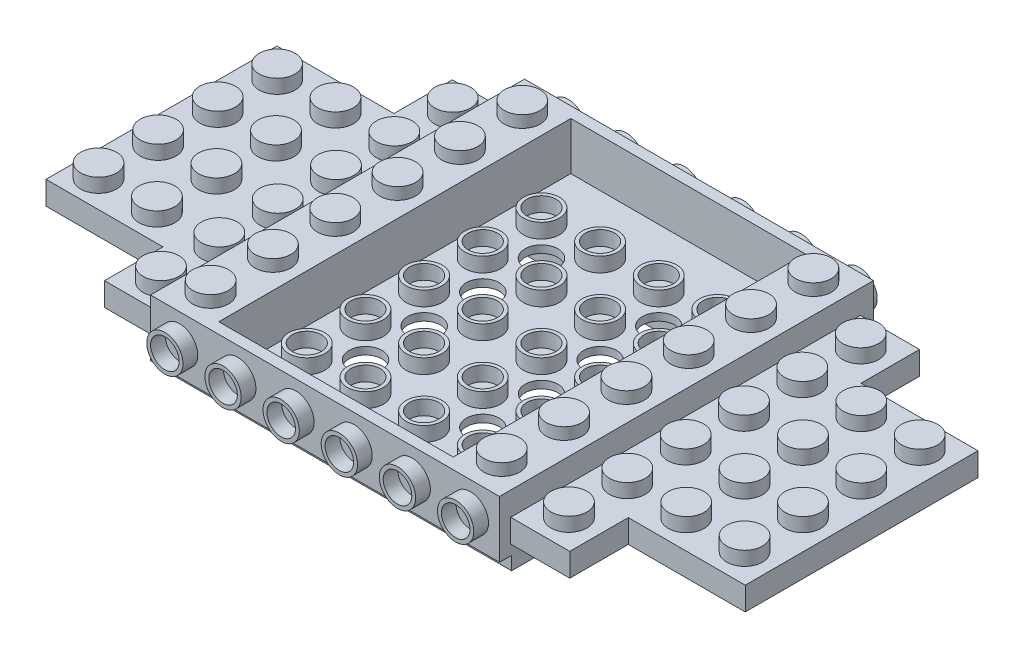
SolidWorks part; units mm, degrees
ref_plane "Front Plane" through (0, 0, 0) normal (0, 0, 1) x (1, 0, 0)
ref_plane "Top Plane" through (0, 0, 0) normal (0, 1, 0) x (1, 0, 0)
ref_plane "Right Plane" through (0, 0, 0) normal (1, 0, 0) x (0, 0, -1)
sketch "Sketch2" plane through (0, 0, 0) normal (0, 1, 0) x (1, 0, 0)
  line L1 (-23.86, 25.57) -> (23.86, 25.57)
  line L2 (-23.86, 25.57) -> (-23.86, -25.57)
  line L3 (-23.86, -25.57) -> (23.86, -25.57)
  line L4 (23.86, 25.57) -> (23.86, -25.57)
  line L5 (-23.86, 25.57) -> (23.86, -25.57) construction
  line L6 (-23.86, -25.57) -> (23.86, 25.57) construction
  point P0 (0, 0)
  dimension "D1" = 51.14
  dimension "D2" = 47.72
extrude "Boss-Extrude1" add sketch "Sketch2" against normal blind 9.64
sketch "Sketch3" plane through (0, 0, 0) normal (0, 1, 0) x (1, 0, 0)
  line L0 (-23.86, 25.57) -> (-23.86, -25.57) construction
  line L1 (-16.03, 24.07) -> (16.03, 24.07)
  line L2 (-16.03, 24.07) -> (-16.03, -24.07)
  line L3 (-16.03, -24.07) -> (16.03, -24.07)
  line L4 (16.03, 24.07) -> (16.03, -24.07)
  line L5 (-16.03, 24.07) -> (16.03, -24.07) construction
  line L6 (-16.03, -24.07) -> (16.03, 24.07) construction
  line L7 (23.86, 25.57) -> (-23.86, 25.57) construction
  point P0 (0, 0)
  dimension "D1" = 7.83
  dimension "D2" = 1.5
extrude "Cut-Extrude1" cut sketch "Sketch3" against normal blind 6.53
sketch "Sketch4" plane through (23.86, 0, 0) normal (1, 0, 0) x (0, 0, -1)
  line L0 (-32.1055, -4.82) -> (30.0315, -4.82) construction
  line L2 (-25.57, 0) -> (25.57, 0) construction
  line L3 (-24.04, -3.23) -> (-24.04, -6.41)
  line L4 (23.79, -3.23) -> (23.79, -6.41)
  line L5 (25.57, -9.64) -> (25.57, 0) construction
  line L6 (-24.04, -6.41) -> (23.79, -6.41)
  line L7 (-24.04, -3.23) -> (23.79, -3.23)
  point P6 (-24.04, -4.82)
  point P9 (23.79, -4.82)
  dimension "D1" = 4.82
  dimension "D2" = 3.18
  dimension "D3" = 3.18
  dimension "D4" = 47.83
  dimension "D5" = 1.78
extrude "Boss-Extrude2" add sketch "Sketch4" along normal blind 8.08
sketch "Sketch5" plane through (23.86, 0, 0) normal (1, 0, 0) x (0, 0, -1)
  line L0 (-25.57, -7.8) -> (-23.91, -7.8)
  line L1 (-25.57, -9.64) -> (-25.57, 0) construction
  line L2 (-23.91, -7.8) -> (-23.91, -9.64)
  line L3 (-25.57, -9.64) -> (25.57, -9.64) construction
  line L4 (0, 5.3017) -> (0, -15.0404) construction
  line L5 (23.91, -7.8) -> (23.91, -9.64)
  line L6 (25.57, -7.8) -> (23.91, -7.8)
  line L7 (-25.57, -7.8) -> (-25.57, -9.64)
  line L8 (-25.57, -9.64) -> (-23.91, -9.64)
  line L9 (23.91, -9.64) -> (25.57, -9.64)
  line L10 (25.57, -9.64) -> (25.57, -7.8)
  dimension "D1" = 1.66
  dimension "D2" = 1.84
extrude "Cut-Extrude2" cut sketch "Sketch5" against normal through all
sketch "Sketch6" plane through (31.94, 0, 0) normal (1, 0, 0) x (0, 0, -1)
  line L0 (-16.04, -3.23) -> (-16.04, -6.41)
  line L1 (23.79, -3.23) -> (-24.04, -3.23) construction
  line L2 (-24.04, -6.41) -> (23.79, -6.41) construction
  line L3 (-16.04, -6.41) -> (15.79, -6.41)
  line L4 (-24.04, -6.41) -> (23.79, -6.41) construction
  line L5 (15.79, -6.41) -> (15.79, -3.23)
  line L6 (23.79, -3.23) -> (-24.04, -3.23) construction
  line L7 (15.79, -3.23) -> (-16.04, -3.23)
  line L8 (23.79, -6.41) -> (23.79, -3.23) construction
  line L9 (-24.04, -3.23) -> (-24.04, -6.41) construction
  point P14 (23.79, -4.82)
  dimension "D1" = 8
  dimension "D2" = 8
extrude "Boss-Extrude3" add sketch "Sketch6" along normal blind 16
sketch "Sketch8" plane through (-23.86, 0, 0) normal (-1, 0, 0) x (0, 0, 1)
  line L0 (-23.79, -4.82) -> (23.79, -4.82) construction
  line L1 (-25.57, 0) -> (25.57, 0) construction
  line L2 (-25.57, -7.8) -> (-25.57, 0) construction
  line L4 (-23.79, -3.23) -> (-23.79, -6.41)
  line L5 (-23.79, -6.41) -> (23.79, -6.41)
  line L6 (23.79, -6.41) -> (23.79, -3.23)
  line L7 (23.79, -3.23) -> (-23.79, -3.23)
  point P6 (0, -4.82)
  point P13 (-23.79, -4.82)
  dimension "D1" = 4.82
  dimension "D2" = 1.78
  dimension "D3" = 3.18
extrude "Boss-Extrude4" add sketch "Sketch8" along normal blind 8.08
sketch "Sketch9" plane through (-31.94, 0, 0) normal (-1, 0, 0) x (0, 0, 1)
  line L0 (-15.79, -3.23) -> (-15.79, -6.41)
  line L1 (23.79, -3.23) -> (-23.79, -3.23) construction
  line L2 (-23.79, -6.41) -> (23.79, -6.41) construction
  line L3 (-15.79, -6.41) -> (15.79, -6.41)
  line L4 (15.79, -6.41) -> (15.79, -3.23)
  line L5 (23.79, -3.23) -> (-23.79, -3.23) construction
  line L6 (15.79, -3.23) -> (-15.79, -3.23)
  line L7 (-23.79, -3.23) -> (-23.79, -6.41) construction
  line L8 (23.79, -6.41) -> (23.79, -3.23) construction
  dimension "D1" = 8
  dimension "D2" = 8
extrude "Boss-Extrude5" add sketch "Sketch9" along normal blind 16
sketch "Sketch12" plane through (0, -3.23, 0) normal (0, 1, 0) x (1, 0, 0)
  line L1 (-31.94, 15.79) -> (-31.94, 23.79) construction
  line L2 (-31.94, 23.79) -> (-23.86, 23.79) construction
  line L4 (-47.94, -15.79) -> (-47.94, 15.79) construction
  circle A0 centre (-27.9, 19.79) radius 2.455
  circle A1 centre (-27.9, 11.8117) radius 2.455
  circle A2 centre (-27.9, 3.8333) radius 2.455
  circle A3 centre (-27.9, -4.145) radius 2.455
  circle A4 centre (-27.9, -12.1233) radius 2.455
  circle A5 centre (-27.9, -20.1017) radius 2.455
  circle A6 centre (-43.9275, 11.8117) radius 2.455
  circle A7 centre (-35.9475, 11.8117) radius 2.455
  circle A8 centre (-36.1106, 3.8333) radius 2.455
  circle A9 centre (-36.2737, -4.145) radius 2.455
  circle A10 centre (-36.4368, -12.1233) radius 2.455
  circle A11 centre (-44.0906, 3.8333) radius 2.455
  circle A12 centre (-44.2537, -4.145) radius 2.455
  circle A13 centre (-44.4168, -12.1233) radius 2.455
  dimension "D3" = 4.91
  dimension "D5" = 7.9783
  dimension "D6" = 4.91
  dimension "D7" = 4.0125
  dimension "D10" = 7.98
  dimension "D11" = 7.98
  dimension "D1" = 4.04
  dimension "D2" = 4
  dimension "D4" = 6
  dimension "D8" = 2
  dimension "D9" = 4
extrude "Boss-Extrude6" add sketch "Sketch12" along normal blind 1.91
sketch "Sketch13" plane through (0, -3.23, 0) normal (0, 1, 0) x (1, 0, 0)
  line L1 (31.94, 23.79) -> (31.94, 15.79) construction
  line L2 (31.94, 23.79) -> (23.86, 23.79) construction
  line L5 (47.94, 15.79) -> (47.94, -16.04) construction
  line L6 (47.94, -16.04) -> (31.94, -16.04) construction
  circle A0 centre (27.9, 19.79) radius 2.455
  circle A2 centre (27.9, 11.81) radius 2.455
  circle A3 centre (27.9, 3.83) radius 2.455
  circle A4 centre (27.9, -4.15) radius 2.455
  circle A5 centre (27.9, -12.13) radius 2.455
  circle A6 centre (27.9, -20.11) radius 2.455
  circle A7 centre (43.94, 11.81) radius 2.455
  circle A8 centre (35.96, 11.81) radius 2.455
  circle A9 centre (35.96, 3.83) radius 2.455
  circle A10 centre (35.96, -4.15) radius 2.455
  circle A11 centre (35.96, -12.13) radius 2.455
  circle A12 centre (43.94, 3.83) radius 2.455
  circle A13 centre (43.94, -4.15) radius 2.455
  circle A14 centre (43.94, -12.13) radius 2.455
  dimension "D1" = 4.04
  dimension "D2" = 4.91
  dimension "D6" = 4.91
  dimension "D7" = 4
  dimension "D11" = 7.98
  dimension "D12" = 7.98
  dimension "D8" = 3.91
  dimension "D3" = 4
  dimension "D4" = 6
  dimension "D9" = 2
  dimension "D10" = 4
extrude "Boss-Extrude7" add sketch "Sketch13" along normal blind 1.91
sketch "Sketch14" plane through (0, -6.41, 0) normal (0, -1, 0) x (1, 0, 0)
  line L0 (-46.34, 14.19) -> (-23.86, 14.19)
  line L1 (-23.86, -23.79) -> (-23.86, 23.79) construction
  line L2 (-46.34, 14.19) -> (-46.34, -14.19)
  line L3 (-46.34, -14.19) -> (-23.86, -14.19)
  line L4 (-23.86, -14.19) -> (-23.86, 14.19)
  line L5 (-47.94, 15.79) -> (-31.94, 15.79) construction
  line L6 (-47.94, -15.79) -> (-31.94, -15.79) construction
  line L7 (-47.94, -15.79) -> (-47.94, 15.79) construction
  dimension "D1" = 1.6
  dimension "D2" = 1.6
  dimension "D3" = 1.6
extrude "Cut-Extrude3" cut sketch "Sketch14" against normal blind 2.25
sketch "Sketch17" plane through (0, -6.41, 0) normal (0, -1, 0) x (1, 0, 0)
  line L0 (-23.86, 15.79) -> (-30.34, 15.79)
  line L1 (-23.86, 14.19) -> (-23.86, 23.79) construction
  line L2 (-30.34, 15.79) -> (-30.34, 22.19)
  line L3 (-30.34, 22.19) -> (-23.86, 22.19)
  line L5 (-31.94, 23.79) -> (-23.86, 23.79) construction
  line L6 (-31.94, 15.79) -> (-31.94, 23.79) construction
  line L7 (-23.86, 14.19) -> (-46.34, 14.19) construction
  line L8 (-23.86, 22.19) -> (-23.86, 15.79)
  line L9 (-59.2264, 0) -> (-14.3327, 0) construction
  line L10 (-23.86, -22.19) -> (-23.86, -15.79)
  line L11 (-23.86, -15.79) -> (-30.34, -15.79)
  line L12 (-30.34, -15.79) -> (-30.34, -22.19)
  line L13 (-30.34, -22.19) -> (-23.86, -22.19)
  dimension "D1" = 1.6
  dimension "D2" = 1.6
  dimension "D3" = 1.6
extrude "Cut-Extrude7" cut sketch "Sketch17" against normal blind 2.25
sketch "Sketch18" plane through (0, -6.41, 0) normal (0, -1, 0) x (1, 0, 0)
  line L0 (23.86, 14.44) -> (46.34, 14.44)
  line L1 (23.86, 24.04) -> (23.86, -23.79) construction
  line L2 (46.34, 14.44) -> (46.34, -14.19)
  line L3 (46.34, -14.19) -> (23.86, -14.19)
  line L4 (23.86, 23.91) -> (23.86, -23.91) construction
  line L5 (23.86, -14.19) -> (23.86, 14.44)
  line L6 (47.94, 16.04) -> (31.94, 16.04) construction
  line L7 (47.94, -15.79) -> (31.94, -15.79) construction
  line L8 (47.94, 16.04) -> (47.94, -15.79) construction
  line L9 (23.86, 22.44) -> (30.34, 22.44)
  line L10 (30.34, 22.44) -> (30.34, 16.04)
  line L11 (30.34, 16.04) -> (23.86, 16.04)
  line L12 (23.86, 16.04) -> (23.86, 22.44)
  line L13 (31.94, 24.04) -> (31.94, 16.04) construction
  line L14 (31.94, 24.04) -> (23.86, 24.04) construction
  line L15 (11.7115, 0) -> (59.8869, 0) construction
  line L16 (23.86, -16.04) -> (23.86, -22.44)
  line L17 (30.34, -16.04) -> (23.86, -16.04)
  line L18 (30.34, -22.44) -> (30.34, -16.04)
  line L19 (23.86, -22.44) -> (30.34, -22.44)
  point P16 (27.1, 16.04)
  point P19 (39.94, 16.04)
  dimension "D1" = 1.6
  dimension "D2" = 1.6
  dimension "D3" = 1.6
  dimension "D4" = 1.6
  dimension "D5" = 1.6
extrude "Cut-Extrude8" cut sketch "Sketch18" against normal blind 2.25
sketch "Sketch20" plane through (0, -4.16, 0) normal (0, -1, 0) x (1, 0, 0)
  line L0 (31.94, 24.04) -> (23.86, 24.04) construction
  line L1 (31.94, 24.04) -> (31.94, 16.04) construction
  circle A0 centre (27.9, 20.04) radius 0.855
  circle A1 centre (27.9, 12.06) radius 0.855
  circle A2 centre (27.9, 4.08) radius 0.855
  circle A3 centre (27.9, -3.9) radius 0.855
  circle A4 centre (27.9, -11.88) radius 0.855
  circle A5 centre (27.9, -19.86) radius 0.855
  circle A6 centre (35.88, -11.88) radius 0.855
  circle A7 centre (35.88, -3.9) radius 0.855
  circle A8 centre (43.86, -11.88) radius 0.855
  circle A9 centre (43.86, -3.9) radius 0.855
  circle A10 centre (35.88, 4.08) radius 0.855
  circle A11 centre (35.88, 12.06) radius 0.855
  circle A12 centre (43.86, 4.08) radius 0.855
  circle A13 centre (43.86, 12.06) radius 0.855
  dimension "D1" = 1.71
  dimension "D3" = 4.04
  dimension "D5" = 7.98
  dimension "D8" = 7.98
  dimension "D9" = 7.98
  dimension "D2" = 4
  dimension "D4" = 6
  dimension "D6" = 3
  dimension "D7" = 3
extrude "Cut-Extrude9" cut sketch "Sketch20" against normal blind 1.64
sketch "Sketch21" plane through (0, -4.16, 0) normal (0, -1, 0) x (1, 0, 0)
  circle A1 centre (-27.9, -19.79) radius 0.855
  circle A3 centre (-27.9, -11.81) radius 0.855
  circle A4 centre (-27.9, -3.83) radius 0.855
  circle A5 centre (-27.9, 4.15) radius 0.855
  circle A6 centre (-27.9, 12.13) radius 0.855
  circle A7 centre (-27.9, 20.11) radius 0.855
  circle A8 centre (-43.9275, -11.8117) radius 0.855
  circle A9 centre (-43.9275, -3.8317) radius 0.855
  circle A10 centre (-43.9275, 4.1483) radius 0.855
  circle A11 centre (-43.9275, 12.1283) radius 0.855
  circle A12 centre (-35.9475, -3.8317) radius 0.855
  circle A13 centre (-35.9475, 4.1483) radius 0.855
  circle A14 centre (-35.9475, 12.1283) radius 0.855
  circle A15 centre (-35.9475, -11.8117) radius 0.855
  dimension "D1" = 1.71
  dimension "D3" = 7.98
  dimension "D4" = 1.71
  dimension "D7" = 7.98
  dimension "D8" = 7.98
  dimension "D2" = 6
  dimension "D5" = 4
  dimension "D6" = 2
extrude "Cut-Extrude10" cut sketch "Sketch21" against normal blind 1.64
sketch "Sketch22" plane through (0, 0, -25.57) normal (0, 0, -1) x (-1, 0, 0)
  line L1 (-23.86, 0) -> (23.86, 0) construction
  line L2 (-23.86, -7.8) -> (-23.86, 0) construction
  circle A0 centre (-19.8833, -3.9) radius 2.48
  circle A1 centre (-19.8833, -3.9) radius 1.955
  circle A2 centre (-11.93, -3.9) radius 1.955
  circle A3 centre (-11.93, -3.9) radius 2.48
  circle A4 centre (-3.9767, -3.9) radius 1.955
  circle A5 centre (-3.9767, -3.9) radius 2.48
  circle A6 centre (3.9767, -3.9) radius 1.955
  circle A7 centre (3.9767, -3.9) radius 2.48
  circle A8 centre (11.93, -3.9) radius 1.955
  circle A9 centre (11.93, -3.9) radius 2.48
  circle A10 centre (19.8833, -3.9) radius 1.955
  circle A11 centre (19.8833, -3.9) radius 2.48
  dimension "D1" = 3.9
  dimension "D2" = 3.9767
  dimension "D3" = 4.96
  dimension "D4" = 3.91
  dimension "D6" = 7.9533
  dimension "D5" = 6
extrude "Boss-Extrude8" add sketch "Sketch22" along normal blind 2.02
sketch "Sketch23" plane through (0, 0, 25.57) normal (0, 0, 1) x (1, 0, 0)
  line L1 (-23.86, 0) -> (23.86, 0) construction
  line L2 (-23.86, -7.8) -> (-23.86, 0) construction
  circle A0 centre (-19.8833, -3.9) radius 2.48
  circle A1 centre (-19.8833, -3.9) radius 1.955
  circle A2 centre (-11.93, -3.9) radius 1.955
  circle A3 centre (-11.93, -3.9) radius 2.48
  circle A4 centre (-3.9767, -3.9) radius 1.955
  circle A5 centre (-3.9767, -3.9) radius 2.48
  circle A6 centre (3.9767, -3.9) radius 1.955
  circle A7 centre (3.9767, -3.9) radius 2.48
  circle A8 centre (11.93, -3.9) radius 1.955
  circle A9 centre (11.93, -3.9) radius 2.48
  circle A10 centre (19.8833, -3.9) radius 1.955
  circle A11 centre (19.8833, -3.9) radius 2.48
  dimension "D1" = 3.9
  dimension "D2" = 3.9767
  dimension "D3" = 4.96
  dimension "D4" = 3.91
  dimension "D6" = 7.9533
  dimension "D5" = 6
extrude "Boss-Extrude9" add sketch "Sketch23" along normal blind 2.02
sketch "Sketch24" plane through (0, 0, 0) normal (0, 1, 0) x (1, 0, 0)
  line L0 (0, 32.3882) -> (0, -28.7765) construction
  line L2 (-23.86, 25.57) -> (-23.86, -25.57) construction
  line L3 (23.86, 25.57) -> (-23.86, 25.57) construction
  circle A0 centre (-19.91, 21.3083) radius 2.455
  circle A1 centre (-19.91, 12.785) radius 2.455
  circle A2 centre (-19.91, 4.2617) radius 2.455
  circle A3 centre (-19.91, -4.2617) radius 2.455
  circle A4 centre (-19.91, -12.785) radius 2.455
  circle A5 centre (-19.91, -21.3083) radius 2.455
  circle A6 centre (19.91, -21.3083) radius 2.455
  circle A7 centre (19.91, -12.785) radius 2.455
  circle A8 centre (19.91, -4.2617) radius 2.455
  circle A9 centre (19.91, 4.2617) radius 2.455
  circle A10 centre (19.91, 12.785) radius 2.455
  circle A11 centre (19.91, 21.3083) radius 2.455
  dimension "D1" = 4.91
  dimension "D5" = 8.5233
  dimension "D2" = 3.95
  dimension "D3" = 4.2617
  dimension "D4" = 6
extrude "Boss-Extrude10" add sketch "Sketch24" along normal blind 1.62
sketch "Sketch25" plane through (0, -9.64, 0) normal (0, -1, 0) x (1, 0, 0)
  line L0 (-23.86, -23.91) -> (-23.86, 23.91) construction
  line L1 (-22.6, 22.36) -> (22.6, 22.36)
  line L2 (-22.6, 22.36) -> (-22.6, 15.8931)
  line L3 (-22.6, 15.8931) -> (22.6, 15.8931)
  line L4 (22.6, 22.36) -> (22.6, 15.8931)
  line L5 (-22.6, 22.36) -> (22.6, 15.8931) construction
  line L6 (-22.6, 15.8931) -> (22.6, 22.36) construction
  line L7 (17.42, 14.4531) -> (22.6, 14.4531)
  line L8 (17.42, 14.4531) -> (17.42, -14.4531)
  line L9 (17.42, -14.4531) -> (22.6, -14.4531)
  line L10 (22.6, 14.4531) -> (22.6, -14.4531)
  line L11 (17.42, 14.4531) -> (22.6, -14.4531) construction
  line L12 (17.42, -14.4531) -> (22.6, 14.4531) construction
  line L13 (-22.6, 14.4531) -> (-17.36, 14.4531)
  line L14 (-22.6, 14.4531) -> (-22.6, -14.4531)
  line L15 (-22.6, -14.4531) -> (-17.36, -14.4531)
  line L16 (-17.36, 14.4531) -> (-17.36, -14.4531)
  line L17 (-22.6, 14.4531) -> (-17.36, -14.4531) construction
  line L18 (-22.6, -14.4531) -> (-17.36, 14.4531) construction
  line L19 (-22.6, -15.8931) -> (22.6, -15.8931)
  line L20 (-22.6, -15.8931) -> (-22.6, -22.36)
  line L21 (-22.6, -22.36) -> (22.6, -22.36)
  line L22 (22.6, -15.8931) -> (22.6, -22.36)
  line L23 (-22.6, -15.8931) -> (22.6, -22.36) construction
  line L24 (-22.6, -22.36) -> (22.6, -15.8931) construction
  line L25 (-15.98, 14.4531) -> (15.98, 14.4531)
  line L26 (-15.98, 14.4531) -> (-15.98, -14.4531)
  line L27 (-15.98, -14.4531) -> (15.98, -14.4531)
  line L28 (15.98, 14.4531) -> (15.98, -14.4531)
  line L29 (-15.98, 14.4531) -> (15.98, -14.4531) construction
  line L30 (-15.98, -14.4531) -> (15.98, 14.4531) construction
  line L31 (-23.86, 23.91) -> (23.86, 23.91) construction
  line L32 (-23.86, -23.91) -> (23.86, -23.91) construction
  point P0 (0, 19.1265)
  point P5 (20.01, 0)
  point P10 (-19.98, 0)
  point P15 (0, -19.1265)
  point P20 (0, 0)
  point P27 (-22.6, 19.1265)
  point P28 (-22.6, 0)
  point P29 (-22.6, -19.1265)
  point P36 (22.6, 19.1265)
  point P37 (22.6, 0)
  point P38 (22.6, -19.1265)
  point P41 (-19.98, 14.4531)
  point P42 (0, 14.4531)
  point P43 (20.01, 14.4531)
  point P44 (-19.98, -14.4531)
  point P45 (0, -14.4531)
  point P46 (20.01, -14.4531)
  dimension "D1" = 1.26
  dimension "D2" = 1.55
  dimension "D3" = 1.55
  dimension "D4" = 1.44
  dimension "D5" = 1.44
  dimension "D6" = 1.38
  dimension "D7" = 31.96
  dimension "D8" = 5.18
  dimension "D9" = 6.4669
extrude "Cut-Extrude11" cut sketch "Sketch25" against normal blind 2.09
sketch "Sketch26" plane through (0, -6.53, 0) normal (0, 1, 0) x (1, 0, 0)
  line L0 (-16.03, 24.07) -> (-16.03, -24.07) construction
  line L4 (-16.03, -24.07) -> (16.03, -24.07) construction
  circle A0 centre (-12.0225, 16.0467) radius 2.465
  circle A1 centre (-12.0225, 16.0467) radius 1.995
  circle A2 centre (-3.9992, 16.0467) radius 1.995
  circle A3 centre (-3.9992, 16.0467) radius 2.465
  circle A4 centre (4.0242, 16.0467) radius 1.995
  circle A5 centre (4.0242, 16.0467) radius 2.465
  circle A6 centre (12.0475, 16.0467) radius 1.995
  circle A7 centre (12.0475, 16.0467) radius 2.465
  circle A8 centre (-3.9992, 8.0233) radius 1.995
  circle A9 centre (-3.9992, 8.0233) radius 2.465
  circle A10 centre (4.0242, 8.0233) radius 1.995
  circle A11 centre (4.0242, 8.0233) radius 2.465
  circle A12 centre (12.0475, 8.0233) radius 1.995
  circle A13 centre (12.0475, 8.0233) radius 2.465
  circle A14 centre (-3.9992, 0) radius 1.995
  circle A15 centre (-3.9992, 0) radius 2.465
  circle A16 centre (4.0242, 0) radius 1.995
  circle A17 centre (4.0242, 0) radius 2.465
  circle A18 centre (12.0475, 0) radius 1.995
  circle A19 centre (12.0475, 0) radius 2.465
  circle A20 centre (-3.9992, -8.0233) radius 1.995
  circle A21 centre (-3.9992, -8.0233) radius 2.465
  circle A22 centre (4.0242, -8.0233) radius 1.995
  circle A23 centre (4.0242, -8.0233) radius 2.465
  circle A24 centre (12.0475, -8.0233) radius 1.995
  circle A25 centre (12.0475, -8.0233) radius 2.465
  circle A26 centre (-3.9992, -16.0467) radius 1.995
  circle A27 centre (-3.9992, -16.0467) radius 2.465
  circle A28 centre (4.0242, -16.0467) radius 1.995
  circle A29 centre (4.0242, -16.0467) radius 2.465
  circle A30 centre (12.0475, -16.0467) radius 1.995
  circle A31 centre (12.0475, -16.0467) radius 2.465
  circle A32 centre (-12.0225, 8.0233) radius 1.995
  circle A33 centre (-12.0225, 8.0233) radius 2.465
  circle A34 centre (-12.0225, 0) radius 1.995
  circle A35 centre (-12.0225, 0) radius 2.465
  circle A36 centre (-12.0225, -8.0233) radius 1.995
  circle A37 centre (-12.0225, -8.0233) radius 2.465
  circle A38 centre (-12.0225, -16.0467) radius 1.995
  circle A39 centre (-12.0225, -16.0467) radius 2.465
  dimension "D1" = 4.93
  dimension "D2" = 3.99
  dimension "D3" = 4.0075
  dimension "D4" = 8.0233
  dimension "D7" = 8.0233
  dimension "D5" = 4
  dimension "D6" = 5
extrude "Boss-Extrude11" add sketch "Sketch26" along normal blind 1.99
sketch "Sketch27" plane through (0, -6.53, 0) normal (0, 1, 0) x (1, 0, 0)
  circle A0 centre (-8.0092, 12.0367) radius 2.25
  circle A1 centre (-3.9992, 16.0467) radius 2.465 construction
  circle A2 centre (-12.0225, 16.0467) radius 2.465 construction
  circle A3 centre (-8.0092, 4.0167) radius 2.25
  circle A4 centre (-8.0092, -4.0033) radius 2.25
  circle A5 centre (-8.0092, -12.0233) radius 2.25
  circle A6 centre (8.0375, 12.0367) radius 2.25
  circle A8 centre (12.0475, 16.0467) radius 2.465 construction
  circle A9 centre (8.0375, 4.0167) radius 2.25
  circle A10 centre (8.0375, -4.0033) radius 2.25
  circle A11 centre (8.0375, -12.0233) radius 2.25
  dimension "D1" = 4.5
  dimension "D2" = 4.01
  dimension "D3" = 4.01
  dimension "D5" = 8.02
  dimension "D6" = 4.5
  dimension "D7" = 4.01
  dimension "D8" = 4.01
  dimension "D9" = 4.5
  dimension "D10" = 4.5
  dimension "D11" = 4.5
  dimension "D4" = 4
extrude "Cut-Extrude14" cut sketch "Sketch27" against normal through all
sketch "Sketch28" plane through (0, -7.55, 0) normal (0, -1, 0) x (1, 0, 0)
  line L1 (17.42, 14.4531) -> (22.6, 14.4531)
  line L2 (17.42, 14.4531) -> (17.42, -14.4531)
  line L3 (17.42, -14.4531) -> (22.6, -14.4531)
  line L4 (22.6, 14.4531) -> (22.6, -14.4531)
  line L5 (17.42, 14.4531) -> (22.6, -14.4531) construction
  line L6 (17.42, -14.4531) -> (22.6, 14.4531) construction
  point P0 (20.01, 0)
  dimension "D1" = 5.18
  dimension "D2" = 28.9062
extrude "Cut-Extrude15" cut sketch "Sketch28" against normal blind 6.2
sketch "Sketch30" plane through (0, -7.55, 0) normal (0, -1, 0) x (1, 0, 0)
  line L1 (-22.6, 14.4531) -> (-17.36, 14.4531)
  line L2 (-22.6, 14.4531) -> (-22.6, -14.4531)
  line L3 (-22.6, -14.4531) -> (-17.36, -14.4531)
  line L4 (-17.36, 14.4531) -> (-17.36, -14.4531)
  line L5 (-22.6, 14.4531) -> (-17.36, -14.4531) construction
  line L6 (-22.6, -14.4531) -> (-17.36, 14.4531) construction
  point P0 (-19.98, 0)
  dimension "D1" = 5.24
  dimension "D2" = 28.9062
extrude "Cut-Extrude16" cut sketch "Sketch30" against normal blind 6.2
sketch "Sketch31" plane through (0, -7.55, 0) normal (0, -1, 0) x (1, 0, 0)
  line L0 (-17.36, 15.8931) -> (-17.36, 22.36)
  line L1 (-22.6, 15.8931) -> (22.6, 15.8931) construction
  line L2 (22.6, 22.36) -> (-22.6, 22.36) construction
  line L3 (-22.6, 22.36) -> (-22.6, 15.8931) construction
  line L5 (17.42, 22.36) -> (17.42, 15.8931)
  line L6 (17.42, 14.4531) -> (17.42, -14.4531) construction
  line L8 (-17.36, 22.36) -> (-22.6, 22.36)
  line L9 (-22.6, 22.36) -> (-22.6, 15.8931)
  line L10 (-22.6, 15.8931) -> (-17.36, 15.8931)
  line L11 (17.42, 22.36) -> (22.6, 22.36)
  line L12 (22.6, 22.36) -> (22.6, 15.8931)
  line L13 (22.6, 15.8931) -> (17.42, 15.8931)
  point P12 (17.42, 0)
  point P13 (17.42, 19.1265)
  dimension "D1" = 5.24
extrude "Cut-Extrude17" cut sketch "Sketch31" against normal blind 6.2
sketch "Sketch32" plane through (0, -7.55, 0) normal (0, -1, 0) x (1, 0, 0)
  line L0 (-17.36, -15.8931) -> (-17.36, -22.36)
  line L1 (22.6, -15.8931) -> (-22.6, -15.8931) construction
  line L2 (-22.6, -22.36) -> (22.6, -22.36) construction
  line L3 (17.42, -15.8931) -> (17.42, -22.36)
  line L5 (-17.36, -14.4531) -> (-17.36, 14.4531) construction
  line L6 (17.42, 14.4531) -> (17.42, -14.4531) construction
  line L7 (-17.36, -15.8931) -> (-22.6, -15.8931)
  line L8 (-22.6, -15.8931) -> (-22.6, -22.36)
  line L9 (-22.6, -22.36) -> (-17.36, -22.36)
  line L10 (17.42, -15.8931) -> (22.6, -15.8931)
  line L11 (22.6, -15.8931) -> (22.6, -22.36)
  line L12 (22.6, -22.36) -> (17.42, -22.36)
  point P12 (-17.36, 0)
  point P13 (-17.36, -19.1265)
  point P14 (17.42, 0)
  point P15 (17.42, -19.1265)
extrude "Cut-Extrude18" cut sketch "Sketch32" against normal blind 6.2
fillet "Fillet1" radius 0.4 4 edges at (-17.36, -7.55, 19.1265) (17.42, -7.55, 19.1265) (17.42, -7.55, -19.1265) (-17.36, -7.55, -19.1265)
ref_plane "Plane1" through (0, -9.45, 0) normal (0, 1, 0) x (1, 0, 0)
sketch "Sketch34" plane through (0, -9.45, 0) normal (0, 1, 0) x (1, 0, 0)
  line L3 (17.02, -22.36) -> (-16.96, -22.36) construction
  line L6 (-23.86, 23.91) -> (-23.86, -23.91) construction
  line L7 (0, -30.1358) -> (0, 31.2636) construction
  line L8 (-49.7786, 0) -> (49.2583, 0) construction
  circle A0 centre (-15.9067, -19.125) radius 1.035
  circle A1 centre (-15.9067, -19.125) radius 1.485
  circle A2 centre (15.9067, -19.125) radius 1.035
  circle A3 centre (15.9067, -19.125) radius 1.485
  circle A4 centre (15.9067, 19.125) radius 1.035
  circle A5 centre (15.9067, 19.125) radius 1.485
  circle A6 centre (-15.9067, 19.125) radius 1.035
  circle A7 centre (-15.9067, 19.125) radius 1.485
  dimension "D2" = 2.97
  dimension "D3" = 2.07
  dimension "D1" = 3.235
  dimension "D4" = 7.9533
extrude "Boss-Extrude13" add sketch "Sketch34" along normal up to vertex (2.3 mm away)
sketch "Sketch35" plane through (0, -4.16, 0) normal (0, -1, 0) x (1, 0, 0)
  line L0 (-49.6498, -3.8317) -> (-25.2439, -3.8317) construction
  line L1 (-48.8593, 4.1483) -> (-25.2439, 4.1483) construction
  line L2 (-23.86, -14.19) -> (-23.86, 14.19) construction
  line L3 (-23.86, -23.91) -> (-23.86, 23.91) construction
  line L5 (-23.86, 11.3683) -> (-23.86, 10.5683)
  line L6 (-23.86, 5.7083) -> (-23.86, 4.9083)
  line L7 (-23.86, -3.0717) -> (-23.86, -2.2717)
  line L8 (-23.86, 2.5883) -> (-23.86, 3.3883)
  line L9 (-23.86, -10.2517) -> (-23.86, -11.0517)
  line L10 (-23.86, -4.5917) -> (-23.86, -5.3917)
  line L11 (0, 26.6804) -> (0, -28.6175) construction
  line L12 (23.86, -4.5917) -> (23.86, -5.3917)
  line L13 (23.86, -10.2517) -> (23.86, -11.0517)
  line L14 (23.86, 2.5883) -> (23.86, 3.3883)
  line L15 (23.86, -3.0717) -> (23.86, -2.2717)
  line L16 (23.86, 5.7083) -> (23.86, 4.9083)
  line L17 (23.86, 11.3683) -> (23.86, 10.5683)
  circle A0 centre (-39.9375, 0.1583) radius 3.23
  circle A1 centre (-39.9375, 0.1583) radius 2.43
  circle A3 centre (-43.9275, 4.1483) radius 0.855 construction
  circle A4 centre (-43.9275, -3.8317) radius 0.855 construction
  circle A5 centre (-31.9575, 0.1583) radius 2.43
  circle A6 centre (-31.9575, 0.1583) radius 3.23
  circle A7 centre (-39.9375, -7.8217) radius 2.43
  circle A8 centre (-39.9375, -7.8217) radius 3.23
  circle A9 centre (-31.9575, -7.8217) radius 3.23
  circle A10 centre (-31.9575, -7.8217) radius 2.43
  circle A11 centre (-31.9575, 8.1383) radius 3.23
  circle A12 centre (-31.9575, 8.1383) radius 2.43
  circle A13 centre (-39.9375, 8.1383) radius 2.43
  circle A14 centre (-39.9375, 8.1383) radius 3.23
  arc A15 (-23.86, 5.7083) -> (-23.86, 10.5683) centre (-23.86, 8.1383) cw
  arc A16 (-23.86, 4.9083) -> (-23.86, 11.3683) centre (-23.86, 8.1383) cw
  arc A17 (-23.86, 3.3883) -> (-23.86, -3.0717) centre (-23.86, 0.1583) ccw
  arc A18 (-23.86, 2.5883) -> (-23.86, -2.2717) centre (-23.86, 0.1583) ccw
  arc A19 (-23.86, -11.0517) -> (-23.86, -4.5917) centre (-23.86, -7.8217) cw
  arc A20 (-23.86, -10.2517) -> (-23.86, -5.3917) centre (-23.86, -7.8217) cw
  arc A21 (23.86, -10.2517) -> (23.86, -5.3917) centre (23.86, -7.8217) ccw
  arc A22 (23.86, -11.0517) -> (23.86, -4.5917) centre (23.86, -7.8217) ccw
  arc A23 (23.86, 2.5883) -> (23.86, -2.2717) centre (23.86, 0.1583) cw
  arc A24 (23.86, 3.3883) -> (23.86, -3.0717) centre (23.86, 0.1583) cw
  arc A25 (23.86, 4.9083) -> (23.86, 11.3683) centre (23.86, 8.1383) ccw
  arc A26 (23.86, 5.7083) -> (23.86, 10.5683) centre (23.86, 8.1383) ccw
  circle A27 centre (39.9375, 8.1383) radius 3.23
  circle A28 centre (39.9375, 8.1383) radius 2.43
  circle A29 centre (31.9575, 8.1383) radius 2.43
  circle A30 centre (31.9575, 8.1383) radius 3.23
  circle A31 centre (31.9575, -7.8217) radius 2.43
  circle A32 centre (31.9575, -7.8217) radius 3.23
  circle A33 centre (39.9375, -7.8217) radius 3.23
  circle A34 centre (39.9375, -7.8217) radius 2.43
  circle A35 centre (31.9575, 0.1583) radius 3.23
  circle A36 centre (31.9575, 0.1583) radius 2.43
  circle A37 centre (39.9375, 0.1583) radius 2.43
  circle A38 centre (39.9375, 0.1583) radius 3.23
  dimension "D1" = 3.99
  dimension "D2" = 3.99
  dimension "D3" = 6.46
  dimension "D4" = 4.86
  dimension "D6" = 7.98
  dimension "D7" = 2.43
  dimension "D8" = 3.23
  dimension "D5" = 2
extrude "Boss-Extrude15" add sketch "Sketch35" along normal offset from surface (2.05 mm away) 0.2 up to face at (-31.428, -6.41, 0)
